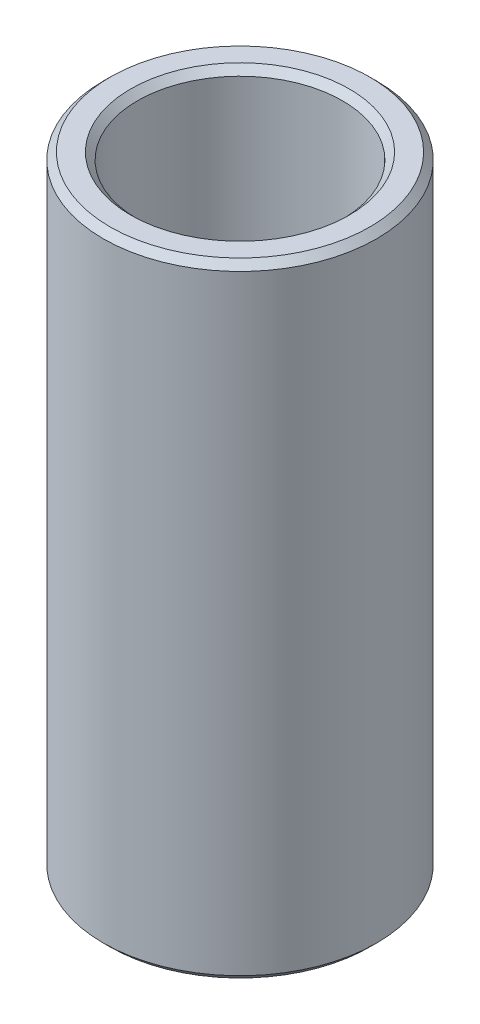
SolidWorks part; units mm, degrees
ref_plane "Front" through (0, 0, 0) normal (0, 0, 1) x (1, 0, 0)
ref_plane "Top" through (0, 0, 0) normal (0, 1, 0) x (1, 0, 0)
ref_plane "Right" through (0, 0, 0) normal (1, 0, 0) x (0, 0, -1)
sketch "Skizze1" plane through (0, 0, 0) normal (0, 1, 0) x (1, 0, 0)
  circle A0 centre (0, 0) radius 4
  circle A1 centre (0, 0) radius 3
  dimension "D1" = 8
  dimension "D2" = 6
extrude "Aufsatz-Linear austragen1" add sketch "Skizze1" along normal blind 18.25
chamfer "Fase1" distance 0.2 angle 45 4 edges at (0, 0, 4) (0, 18.25, 4) (0, 0, 3) (0, 18.25, 3)
